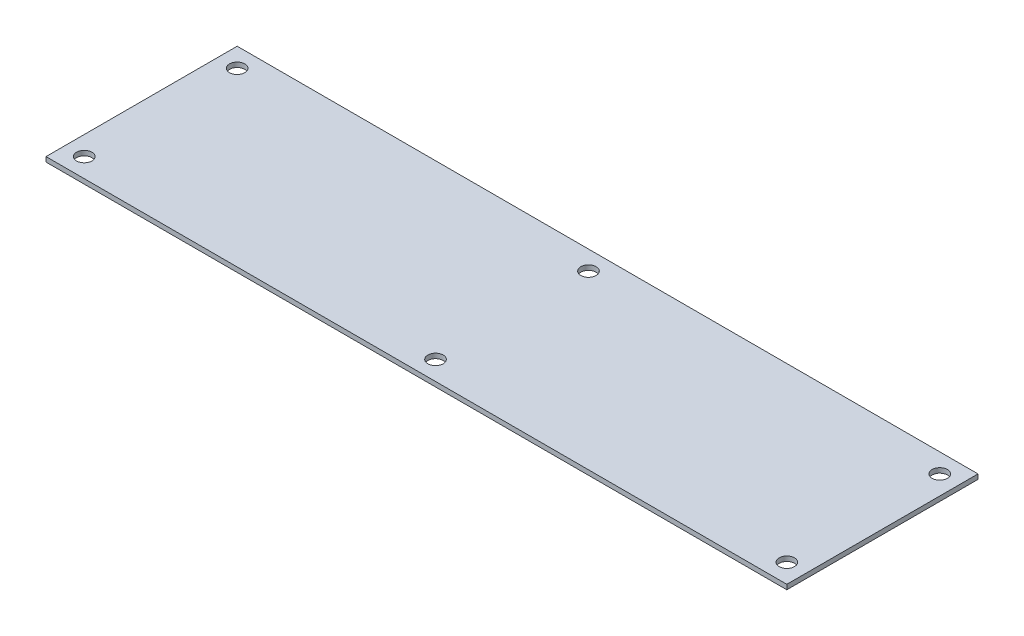
SolidWorks part; units mm, degrees
ref_plane "Спереди" through (0, 0, 0) normal (0, 0, 1) x (1, 0, 0)
ref_plane "Сверху" through (0, 0, 0) normal (0, 1, 0) x (1, 0, 0)
ref_plane "Справа" through (0, 0, 0) normal (1, 0, 0) x (0, 0, -1)
sketch "Эскиз1" plane through (0, 0, 0) normal (0, 1, 0) x (1, 0, 0)
  line L1 (77.5, -20) -> (-77.5, -20)
  line L2 (77.5, -20) -> (77.5, 20)
  line L3 (77.5, 20) -> (-77.5, 20)
  line L4 (-77.5, -20) -> (-77.5, 20)
  line L5 (77.5, -20) -> (-77.5, 20) construction
  line L6 (77.5, 20) -> (-77.5, -20) construction
  point P0 (0, 0)
  dimension "D1" = 155
  dimension "D2" = 40
extrude "Бобышка-Вытянуть1" add sketch "Эскиз1" along normal blind 1
sketch "Эскиз2" plane through (0, 1, 0) normal (0, 1, 0) x (1, 0, 0)
  line L0 (77.5, 20) -> (-77.5, 20) construction
  line L1 (-77.5, 20) -> (-77.5, -20) construction
  line L2 (-77.5, -20) -> (77.5, -20) construction
  line L3 (77.5, -20) -> (77.5, 20) construction
  circle A0 centre (-73.5, 16) radius 1.6
  circle A1 centre (-73.5, -16) radius 1.6
  circle A2 centre (73.5, 16) radius 1.6
  circle A3 centre (73.5, -16) radius 1.6
  circle A4 centre (0, 16) radius 1.6
  circle A5 centre (0, -16) radius 1.6
  dimension "D3" = 3.2
  dimension "D6" = 3.2
  dimension "D9" = 3.2
  dimension "D12" = 3.2
  dimension "D15" = 3.2
  dimension "D18" = 3.2
  dimension "D1" = 4
  dimension "D2" = 4
  dimension "D4" = 4
  dimension "D5" = 4
  dimension "D7" = 4
  dimension "D8" = 4
  dimension "D10" = 4
  dimension "D11" = 4
  dimension "D13" = 4
  dimension "D14" = 0
  dimension "D16" = 0
  dimension "D17" = 4
extrude "Вырез-Вытянуть1" cut sketch "Эскиз2" against normal through all
